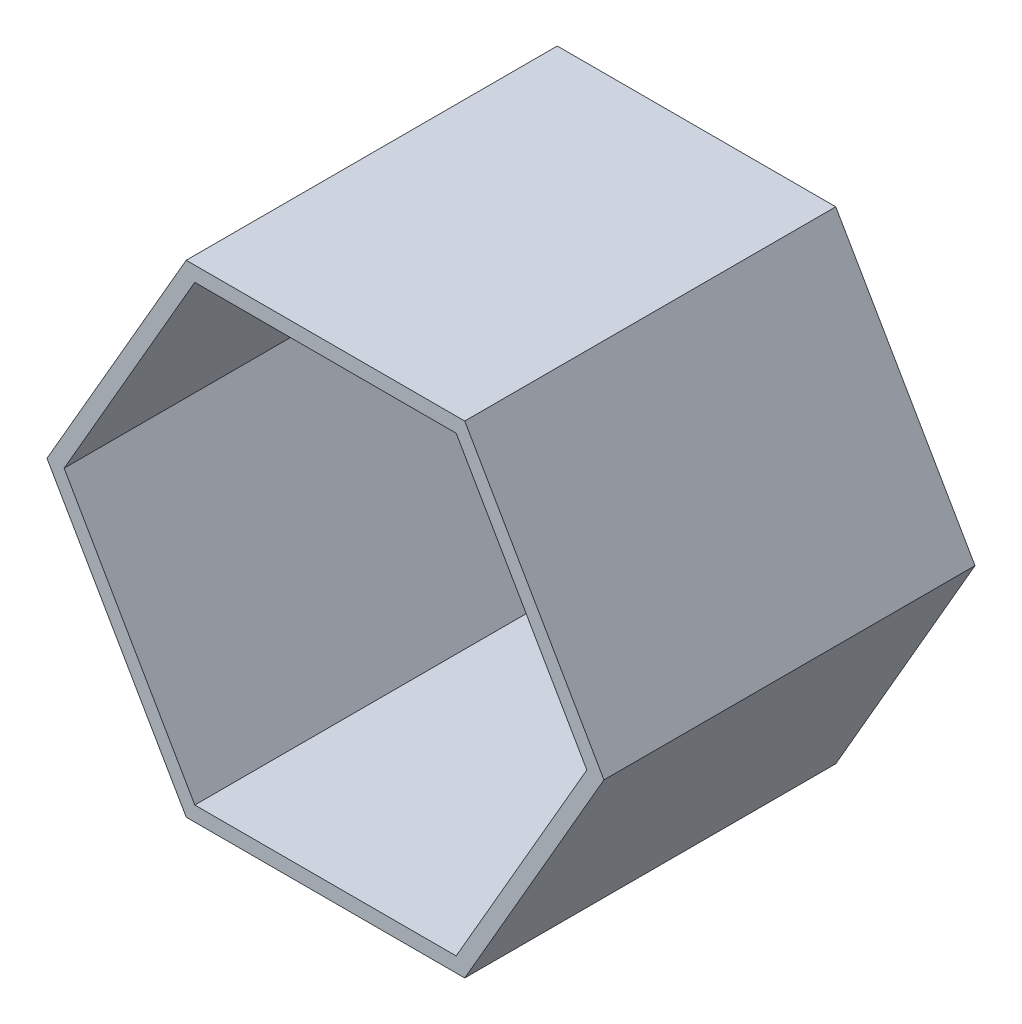
SolidWorks part; units mm, degrees
ref_plane "Alzado" through (0, 0, 0) normal (0, 0, 1) x (1, 0, 0)
ref_plane "Planta" through (0, 0, 0) normal (0, 1, 0) x (1, 0, 0)
ref_plane "Vista lateral" through (0, 0, 0) normal (1, 0, 0) x (0, 0, -1)
sketch "Croquis1" plane through (0, 0, 0) normal (0, 0, 1) x (1, 0, 0)
  line L1 (-19.7954, 11.7001) -> (-25.4246, 21.4501)
  line L2 (-25.4246, 21.4501) -> (-36.6829, 21.4501)
  line L3 (-36.6829, 21.4501) -> (-42.312, 11.7001)
  line L4 (-42.312, 11.7001) -> (-36.6829, 1.9501)
  line L5 (-36.6829, 1.9501) -> (-25.4246, 1.9501)
  line L6 (-25.4246, 1.9501) -> (-19.7954, 11.7001)
  line L7 (-20.4882, 11.7001) -> (-25.771, 20.8501)
  line L8 (-25.771, 20.8501) -> (-36.3365, 20.8501)
  line L9 (-36.3365, 20.8501) -> (-41.6192, 11.7001)
  line L10 (-41.6192, 11.7001) -> (-36.3365, 2.5501)
  line L11 (-36.3365, 2.5501) -> (-25.771, 2.5501)
  line L12 (-25.771, 2.5501) -> (-20.4882, 11.7001)
  circle A0 centre (-31.0537, 11.7001) radius 9.75 construction
  circle A1 centre (-31.0537, 11.7001) radius 9.15 construction
  dimension "D1" = 18.3
  dimension "D2" = 19.5
extrude "Saliente-Extruir1" add sketch "Croquis1" along normal blind 15
